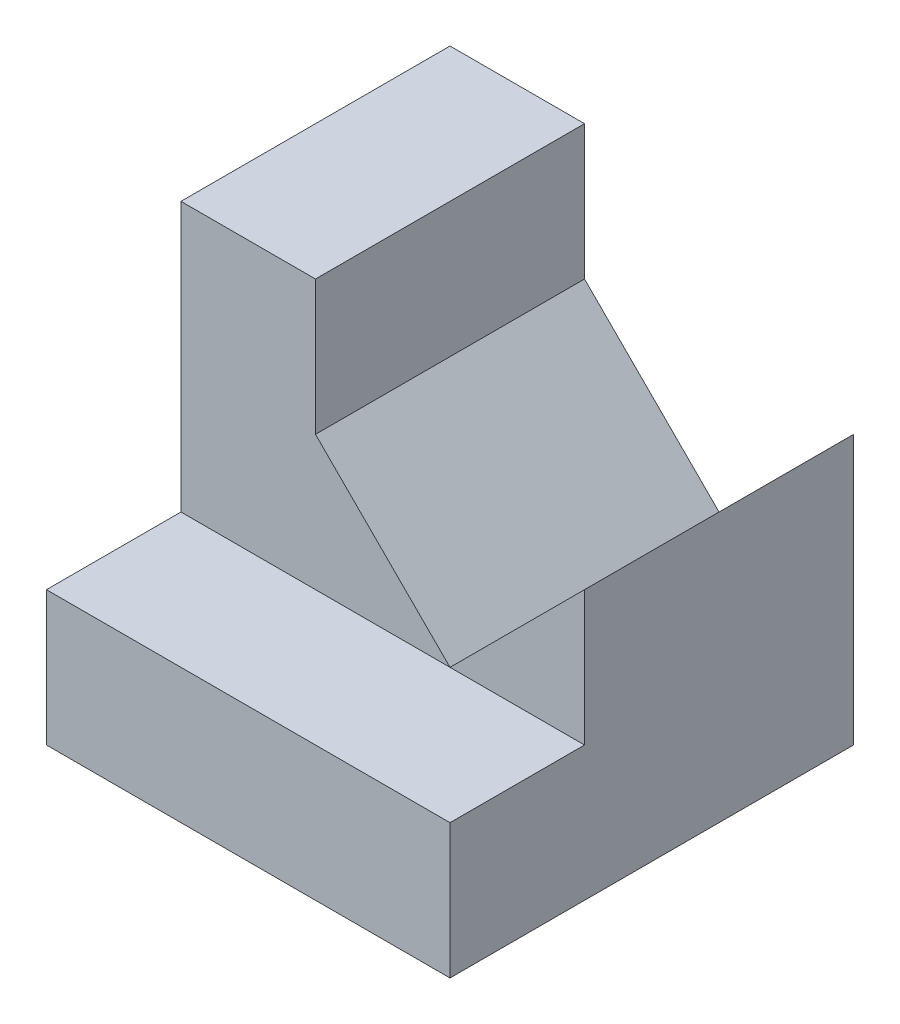
SolidWorks part; units mm, degrees
ref_plane "前基準面" through (0, 0, 0) normal (0, 0, 1) x (1, 0, 0)
ref_plane "上基準面" through (0, 0, 0) normal (0, 1, 0) x (1, 0, 0)
ref_plane "右基準面" through (0, 0, 0) normal (1, 0, 0) x (0, 0, -1)
sketch "草圖1" plane through (0, 0, 0) normal (0, 0, 1) x (1, 0, 0)
  line L1 (0, 0) -> (30, 0)
  line L2 (0, 0) -> (0, 30)
  line L3 (0, 30) -> (30, 30)
  line L4 (30, 0) -> (30, 30)
  dimension "D1" = 30
  dimension "D2" = 30
extrude "填料-伸1" add sketch "草圖1" against normal blind 30
sketch "草圖28" plane through (0, 0, 0) normal (0, 0, 1) x (1, 0, 0)
  line L0 (10, 30) -> (10, 20)
  line L1 (30, 30) -> (0, 30) construction
  line L2 (10, 20) -> (20, 10)
  line L3 (20, 10) -> (30, 20)
  line L4 (30, 0) -> (30, 30) construction
  line L5 (30, 0) -> (30, 30)
  line L6 (30, 30) -> (0, 30)
  line L7 (0, 30) -> (0, 0) construction
  line L8 (0, 0) -> (30, 0) construction
  line L10 (10, 30) -> (30, 30)
  line L11 (10, 30) -> (10, 20)
  line L12 (10, 20) -> (30, 20)
  line L13 (30, 30) -> (30, 20)
  line M6 (30, 0) -> (30, 30)
  line M7 (30, 30) -> (0, 30)
  dimension "D1" = 10
  dimension "D2" = 10
  dimension "D3" = 20
  dimension "D6" = 10
extrude "除料-伸長18" cut sketch "草圖28" against normal through all contours L0 L12 M6 M7 | L12 L2 L3
sketch "草圖29" plane through (30, 0, 0) normal (1, 0, 0) x (0, 0, -1)
  line L0 (30, 30) -> (0, 30) construction
  line L2 (0, 10) -> (10, 10)
  line L3 (0, 10) -> (0, 30)
  line L4 (30, 20) -> (0, 20)
  line L5 (0, 20) -> (0, 0)
  line L6 (0, 0) -> (30, 0)
  line L7 (30, 0) -> (30, 20)
  line L8 (30, 20) -> (0, 20)
  line L9 (0, 20) -> (0, 0)
  line L10 (0, 0) -> (30, 0)
  line L11 (30, 0) -> (30, 20)
  line L12 (0, 30) -> (10, 30)
  line L13 (10, 10) -> (10, 30)
  line M8 (0, 20) -> (0, 0)
  dimension "D2" = 20
  dimension "D3" = 10
  dimension "D1" = 0
extrude "除料-伸長19" cut sketch "草圖29" against normal through all contours L8 L13 L12 L3 | L2 L13 L8 M8
